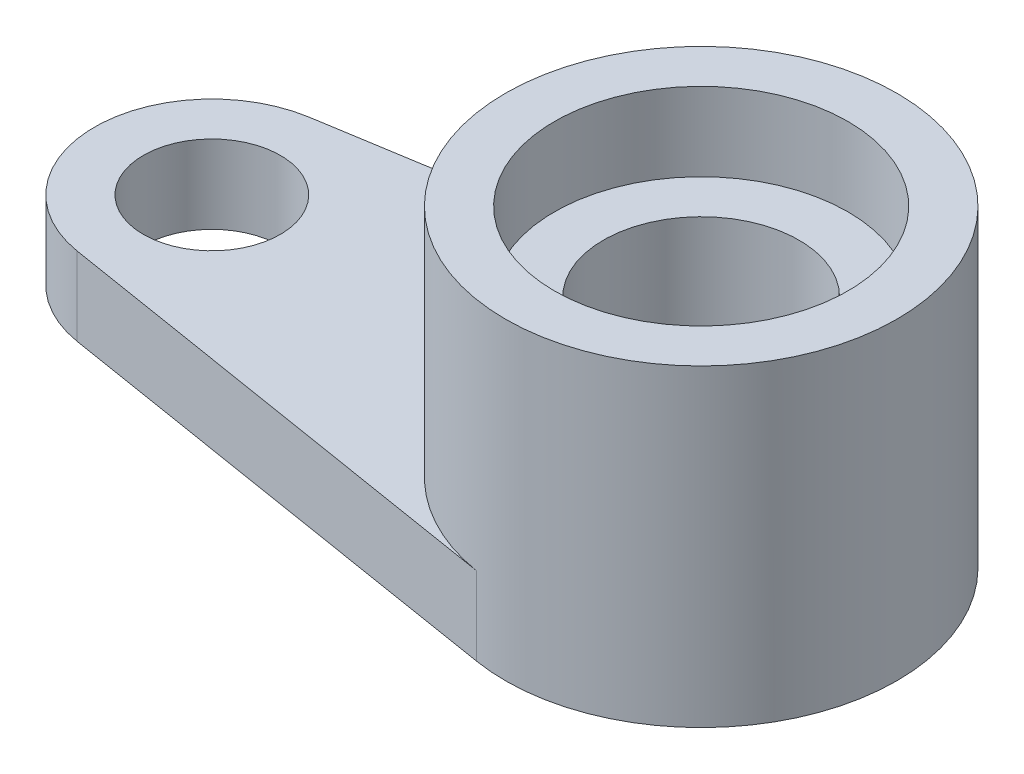
SolidWorks part; units mm, degrees
ref_plane "前视基准面" through (0, 0, 0) normal (0, 0, 1) x (1, 0, 0)
ref_plane "上视基准面" through (0, 0, 0) normal (0, 1, 0) x (1, 0, 0)
ref_plane "右视基准面" through (0, 0, 0) normal (1, 0, 0) x (0, 0, -1)
sketch "草图2" plane through (0, 0, 0) normal (0, 1, 0) x (1, 0, 0)
  line L0 (-51.92, 11.8454) -> (-3.2, 19.7423)
  line L1 (-51.92, -11.8454) -> (-3.2, -19.7423)
  circle A0 centre (0, 0) radius 20
  circle A1 centre (-50, 0) radius 12
  dimension "D1" = 40
  dimension "D2" = 24
extrude "凸台-拉伸3" add sketch "草图2" along normal blind 8 contours A1 L1 A0 L0 | A1 | A0 L1
sketch "草图5" plane through (0, 0, 0) normal (0, 1, 0) x (1, 0, 0)
  circle A0 centre (0, 0) radius 20
extrude "凸台-拉伸4" add sketch "草图5" along normal blind 32 contours A0
sketch "草图7" plane through (0, 32, 0) normal (0, 1, 0) x (1, 0, 0)
  circle A0 centre (0, 0) radius 15
extrude "切除-拉伸1" cut sketch "草图7" against normal blind 8
sketch "草图8" plane through (0, 0, 0) normal (0, 1, 0) x (1, 0, 0)
  circle A0 centre (0, 0) radius 10
extrude "切除-拉伸2" cut sketch "草图8" along normal blind 38 contours A0
sketch "草图9" plane through (0, 0, 0) normal (0, 1, 0) x (1, 0, 0)
  circle A0 centre (-50, 0) radius 7
extrude "切除-拉伸4" cut sketch "草图9" along normal blind 18
